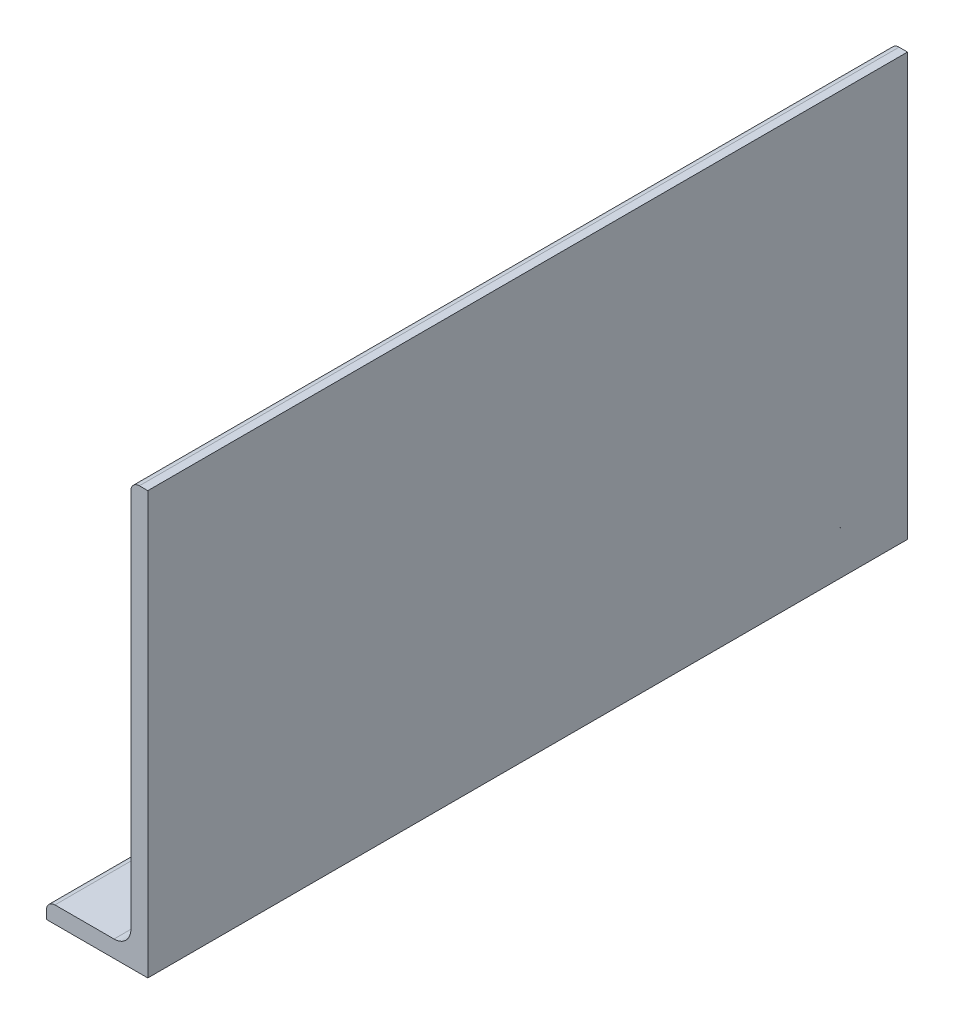
SolidWorks part; units mm, degrees
ref_plane "Front Plane" through (0, 0, 0) normal (0, 0, 1) x (1, 0, 0)
ref_plane "Top Plane" through (0, 0, 0) normal (0, 1, 0) x (1, 0, 0)
ref_plane "Right Plane" through (0, 0, 0) normal (1, 0, 0) x (0, 0, -1)
sketch "Sketch1" plane through (0, 0, 0) normal (0, 0, 1) x (1, 0, 0)
  line L0 (1262.5075, -206.0487) -> (1262.5075, -256.0487)
  line L1 (1262.5075, -256.0487) -> (1250.5075, -256.0487)
  line L2 (1250.5075, -256.0487) -> (1250.5075, -254.0487)
  line L3 (1250.5075, -254.0487) -> (1260.5075, -254.0487)
  line L4 (1260.5075, -254.0487) -> (1260.5075, -206.0487)
  line L5 (1262.5075, -206.0487) -> (1260.5075, -206.0487)
  dimension "D1" = 50
  dimension "D2" = 2
  dimension "D3" = 2
  dimension "D4" = 12
extrude "Boss-Extrude1" add sketch "Sketch1" along normal blind 90
fillet "Fillet1" radius 1 2 edges at (1250.5075, -254.0487, 45) (1260.5075, -206.0487, 45)
fillet "Fillet2" radius 2 1 edges at (1260.5075, -254.0487, 45)
sketch "Sketch2" plane through (0, -254.0487, 0) normal (0, 1, 0) x (1, 0, 0)
  line L0 (1262.5075, -90) -> (1262.5075, 0) construction
  line L1 (1258.5075, -90) -> (1251.5075, -90) construction
  line L2 (1258.5075, 0) -> (1251.5075, 0) construction
  circle A0 centre (1255.0075, -70) radius 1.6
  circle A1 centre (1255.0075, -20) radius 1.6
  dimension "D1" = 3.2
  dimension "D2" = 3.2
  dimension "D3" = 7.5
  dimension "D4" = 20
  dimension "D5" = 20
  dimension "D6" = 7.5
extrude "Cut-Extrude1" cut sketch "Sketch2" against normal blind 10
